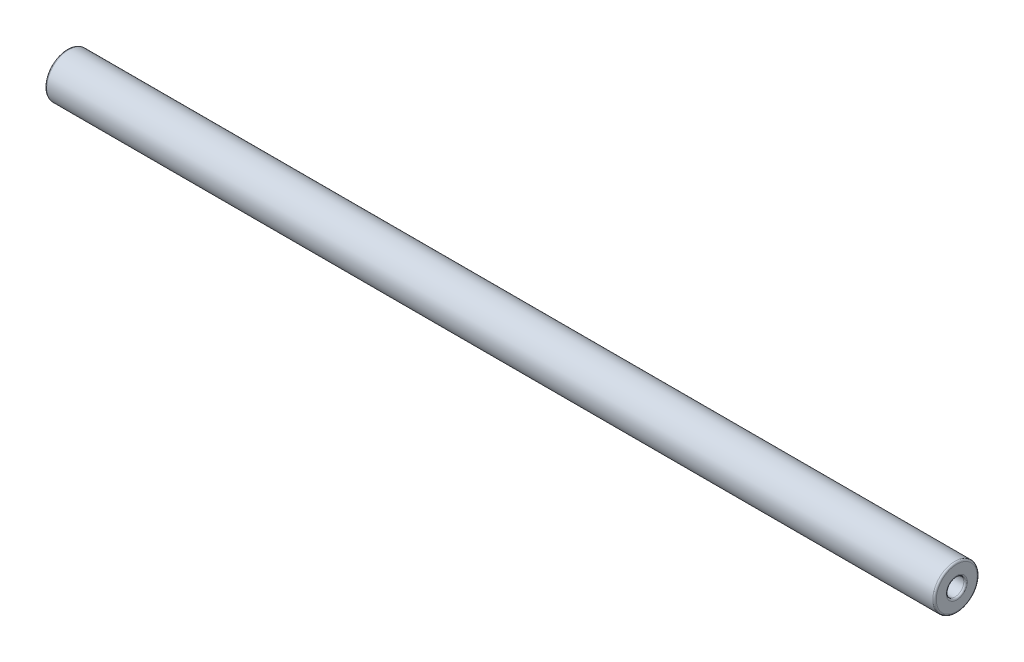
SolidWorks part; units mm, degrees
ref_plane "Front Plane" through (0, 0, 0) normal (0, 0, 1) x (1, 0, 0)
ref_plane "Top Plane" through (0, 0, 0) normal (0, 1, 0) x (1, 0, 0)
ref_plane "Right Plane" through (0, 0, 0) normal (1, 0, 0) x (0, 0, -1)
sketch "Sketch1" plane through (0, 0, 0) normal (1, 0, 0) x (0, 0, -1)
  circle A0 centre (0, 0) radius 6.35
  circle A1 centre (0, 0) radius 2.5
  dimension "D1" = 5
  dimension "D2" = 12.7
extrude "Boss-Extrude1" add sketch "Sketch1" along normal mid plane 254
fillet "Fillet1" radius 0.5 4 edges at (-127, 0, -2.5) (-127, 0, -6.35) (127, 0, -2.5) (127, 0, -6.35)
